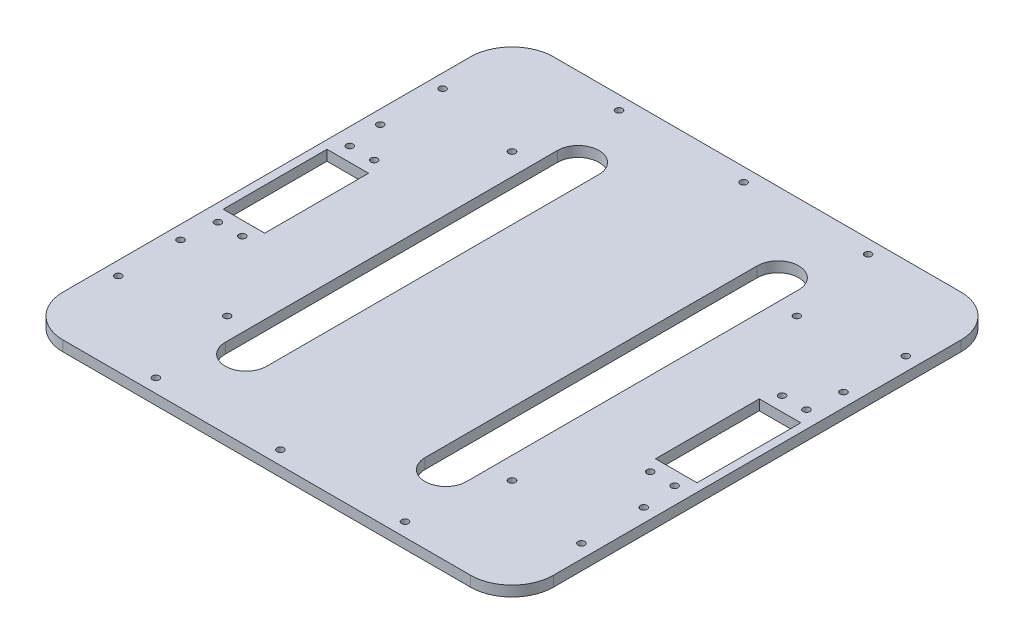
SolidWorks part; units mm, degrees
ref_plane "Front Plane" through (0, 0, 0) normal (0, 0, 1) x (1, 0, 0)
ref_plane "Top Plane" through (0, 0, 0) normal (0, 1, 0) x (1, 0, 0)
ref_plane "Right Plane" through (0, 0, 0) normal (1, 0, 0) x (0, 0, -1)
sketch "Sketch1" plane through (0, 0, 0) normal (0, 1, 0) x (1, 0, 0)
  line L1 (-150, 150) -> (150, 150)
  line L2 (-150, 150) -> (-150, -150)
  line L3 (-150, -150) -> (150, -150)
  line L4 (150, 150) -> (150, -150)
  line L5 (-150, 150) -> (150, -150) construction
  line L6 (-150, -150) -> (150, 150) construction
  point P0 (0, 0)
  dimension "D1" = 300
  dimension "30cm" = 300
extrude "Boss-Extrude1" add sketch "Sketch1" along normal blind 6.35
sketch "Sketch2" plane through (0, 6.35, 0) normal (0, 1, 0) x (1, 0, 0)
  line L0 (127.775, -101.2886) -> (127.775, 49898.7114) construction
  line L1 (-127.775, 7.7624) -> (-127.775, 50007.7624) construction
  line L2 (-244.363, -127.775) -> (49755.637, -127.775) construction
  line L3 (-269.6272, 127.775) -> (49730.3728, 127.775) construction
  line L4 (-150, 150) -> (-150, -150) construction
  line L5 (-150, -150) -> (150, -150) construction
  line L6 (150, -150) -> (150, 150) construction
  line L7 (150, 150) -> (-150, 150) construction
  line L8 (0, 150) -> (0, 50150) construction
  line L9 (-150, 0) -> (-50150, 0) construction
  line L19 (-61.1, -101.6) -> (-61.1, 101.6) construction
  line L23 (-150, 150) -> (150, -150) construction
  line L25 (-73.8, -101.6) -> (-73.8, 101.6)
  line L26 (-48.4, -101.6) -> (-48.4, 101.6)
  line L27 (61.1, -101.6) -> (61.1, 101.6) construction
  line L28 (73.8, -101.6) -> (73.8, 101.6)
  line L29 (48.4, -101.6) -> (48.4, 101.6)
  circle A0 centre (-87.1382, 87.1382) radius 2.0828
  circle A1 centre (87.1382, 87.1382) radius 2.0828
  circle A2 centre (87.1382, -87.1382) radius 2.0828
  circle A3 centre (-87.1382, -87.1382) radius 2.0828
  circle A4 centre (-141.6688, 99.2) radius 2.0828
  circle A5 centre (-141.6688, 61.1) radius 2.0828
  circle A6 centre (-141.6688, -99.2) radius 2.0828
  circle A7 centre (-141.6688, -61.1) radius 2.0828
  circle A8 centre (-76.2, -141.6688) radius 2.0828
  circle A9 centre (76.2, -141.6688) radius 2.0828
  circle A10 centre (0, -141.6688) radius 2.0828
  circle A11 centre (-76.2, 141.6688) radius 2.0828
  circle A12 centre (0, 141.6688) radius 2.0828
  circle A13 centre (76.2, 141.6688) radius 2.0828
  circle A14 centre (141.6688, 99.2) radius 2.0828
  circle A15 centre (141.6688, 61.1) radius 2.0828
  circle A16 centre (141.6688, -99.2) radius 2.0828
  circle A17 centre (141.6688, -61.1) radius 2.0828
  circle A18 centre (-139.6622, 40.4492) radius 2.0828
  circle A19 centre (-124.7778, 40.4492) radius 2.0828
  circle A20 centre (-139.6622, -40.2212) radius 2.0828
  circle A21 centre (-124.7778, -40.2212) radius 2.0828
  circle A22 centre (124.7778, 40.4492) radius 2.0828
  circle A23 centre (139.6622, 40.4492) radius 2.0828
  circle A24 centre (124.7778, -40.2212) radius 2.0828
  circle A25 centre (139.6622, -40.2212) radius 2.0828
  arc A28 (-73.8, -101.6) -> (-48.4, -101.6) centre (-61.1, -101.6) ccw
  arc A29 (-48.4, 101.6) -> (-73.8, 101.6) centre (-61.1, 101.6) ccw
  arc A30 (73.8, -101.6) -> (48.4, -101.6) centre (61.1, -101.6) cw
  arc A31 (48.4, 101.6) -> (73.8, 101.6) centre (61.1, 101.6) cw
  point P17 (0, 150)
  point P21 (-150, 0)
  point P24 (-61.1, 0)
  point P110 (61.1, 0)
  line B0 (119.52, 0) -> (-119.52, 0) construction
  line B1 (144.92, -31.75) -> (119.52, -31.75)
  line B2 (144.92, -31.75) -> (144.92, 31.75)
  line B3 (144.92, 31.75) -> (119.52, 31.75)
  line B4 (119.52, -31.75) -> (119.52, 31.75)
  line B5 (-119.52, -31.75) -> (-144.92, -31.75)
  line B6 (-119.52, -31.75) -> (-119.52, 31.75)
  line B7 (-119.52, 31.75) -> (-144.92, 31.75)
  line B8 (-144.92, -31.75) -> (-144.92, 31.75)
  line B9 (0, -51.8106) -> (0, -50051.8106) construction
  dimension "D8" = 4.1656
  dimension "D6" = 12.7
  dimension "D1" = 22.225
  dimension "D2" = 22.225
  dimension "D3" = 22.225
  dimension "D4" = 22.225
  dimension "D5" = 203.2
  dimension "D7" = 76.2
  dimension "D9" = 88.9
sketch_block_instance "Block2-1"
sketch_block "Block2" parameters "D1"=20.32, "D2"=20.32, "D3"=246.66, "D4"=54.356
extrude "Cut-Extrude1" cut sketch "Sketch2" against normal through all
fillet "Fillet1" radius 25.4 4 edges at (-150, 3.175, -150) (-150, 3.175, 150) (150, 3.175, 150) (150, 3.175, -150)
